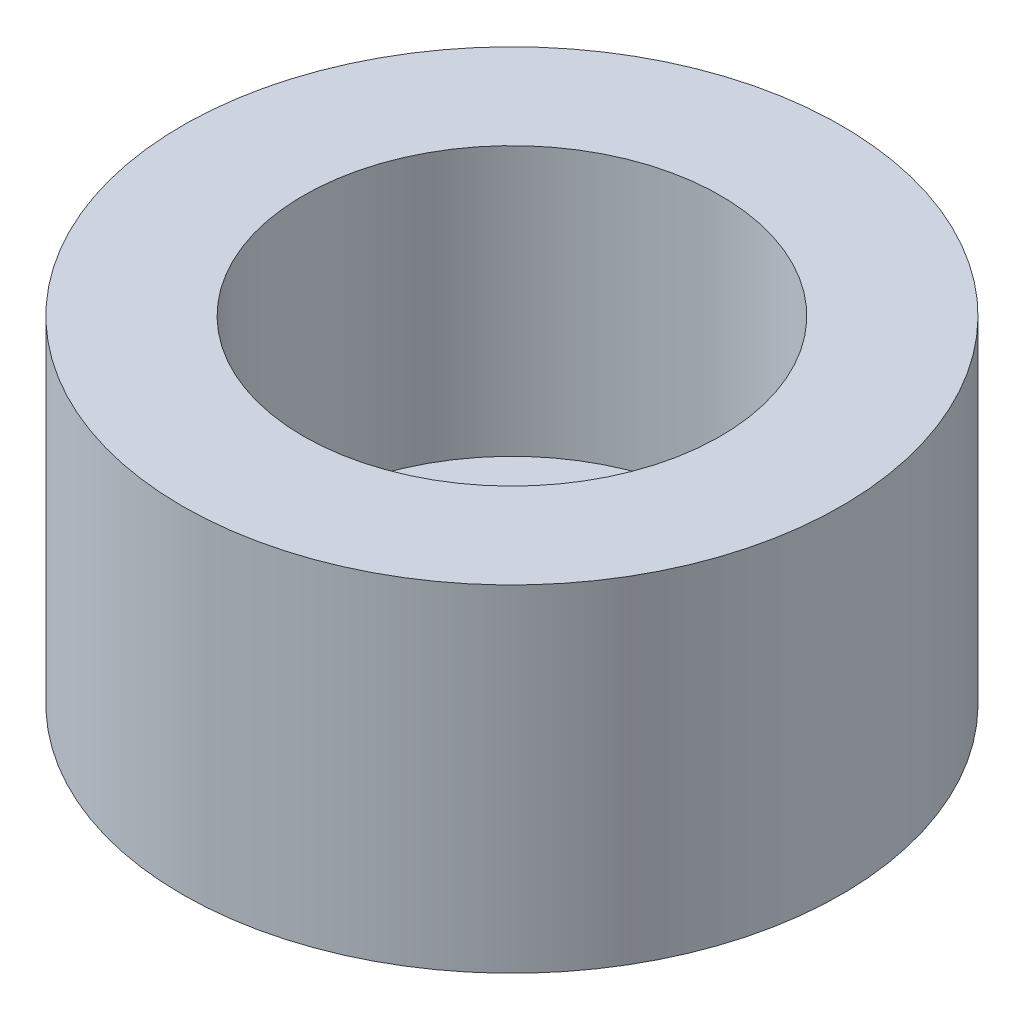
SolidWorks part; units mm, degrees
ref_plane "Front Plane" through (0, 0, 0) normal (0, 0, 1) x (1, 0, 0)
ref_plane "Top Plane" through (0, 0, 0) normal (0, 1, 0) x (1, 0, 0)
ref_plane "Right Plane" through (0, 0, 0) normal (1, 0, 0) x (0, 0, -1)
sketch "Sketch1" plane through (0, 0, 0) normal (0, 1, 0) x (1, 0, 0)
  line L0 (-9.7681, 0) -> (10.1509, 0) construction
  circle A0 centre (0, 0) radius 2.45
  point P4 (0, 0)
  dimension "D1" = 4.9
extrude "Boss-Extrude1" add sketch "Sketch1" along normal blind 2.5
sketch "Sketch2" plane through (0, 2.5, 0) normal (0, 1, 0) x (1, 0, 0)
  circle A0 centre (0, 0) radius 1.55
  dimension "D1" = 3.1
extrude "Cut-Extrude1" cut sketch "Sketch2" against normal blind 2
